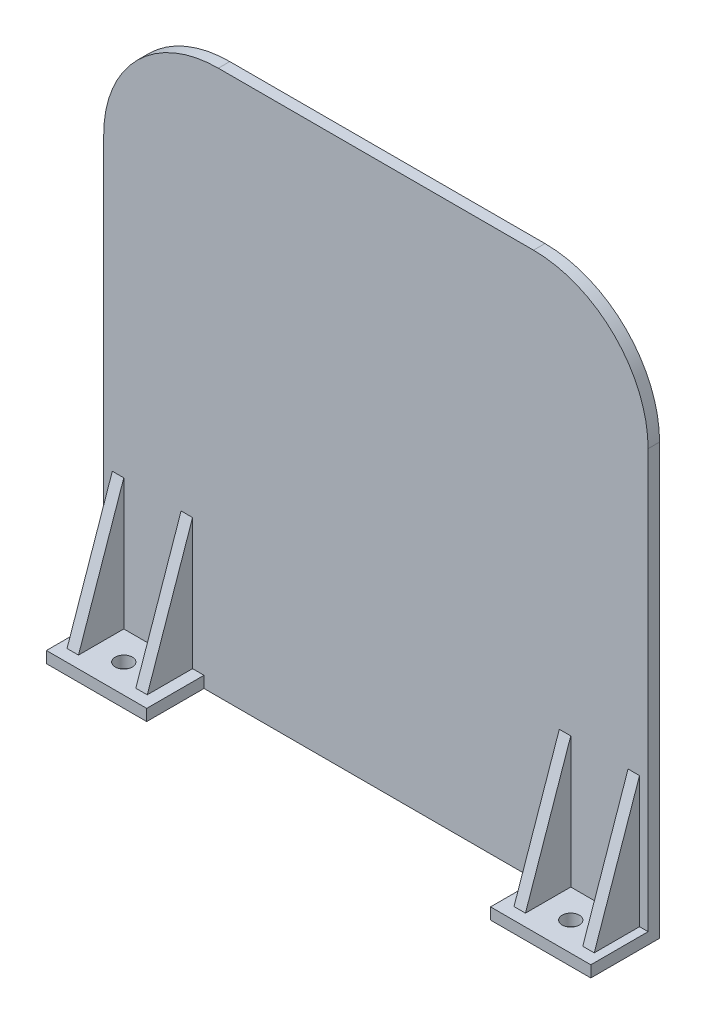
SolidWorks part; units mm, degrees
ref_plane "前视基准面" through (0, 0, 0) normal (0, 0, 1) x (1, 0, 0)
ref_plane "上视基准面" through (0, 0, 0) normal (0, 1, 0) x (1, 0, 0)
ref_plane "右视基准面" through (0, 0, 0) normal (1, 0, 0) x (0, 0, -1)
sketch "草图1" plane through (0, 0, 0) normal (0, 0, 1) x (1, 0, 0)
  line L1 (-47.5, -47.5) -> (47.5, -47.5)
  line L2 (-47.5, -47.5) -> (-47.5, 47.5)
  line L3 (-47.5, 47.5) -> (47.5, 47.5)
  line L4 (47.5, -47.5) -> (47.5, 47.5)
  line L5 (-47.5, -47.5) -> (47.5, 47.5) construction
  line L6 (-47.5, 47.5) -> (47.5, -47.5) construction
  point P0 (0, 0)
  dimension "D1" = 95
  dimension "D2" = 95
extrude "凸台-拉伸1" add sketch "草图1" along normal blind 2
sketch "草图2" plane through (0, 0, 2) normal (0, 0, 1) x (1, 0, 0)
  line L0 (47.5, -47.5) -> (47.5, 47.5) construction
  line L1 (-47.5, -47.5) -> (47.5, -47.5)
  line L2 (-47.5, -47.5) -> (-47.5, -45.5)
  line L3 (-47.5, -45.5) -> (47.5, -45.5)
  line L4 (47.5, -47.5) -> (47.5, -45.5)
  dimension "D1" = 2
extrude "凸台-拉伸2" add sketch "草图2" along normal blind 10
fillet "圆角1" radius 20 2 edges at (47.5, 47.5, 1) (-47.5, 47.5, 1)
sketch "草图3" plane through (0, -45.5, 0) normal (0, 1, 0) x (1, 0, 0)
  line L2 (30, -2) -> (30, -12)
  line L4 (-30, -2) -> (-30, -12)
  line L5 (-30, -2) -> (30, -2)
  line L6 (47.5, -2) -> (-47.5, -2) construction
  line L10 (-30, -2) -> (-30, -12)
  line L12 (47.5, -12) -> (-47.5, -12) construction
  line L16 (30, -2) -> (30, -12)
  line L17 (30, -12) -> (-30, -12)
  dimension "D1" = 60
  dimension "D2" = 30
extrude "切除-拉伸1" cut sketch "草图3" against normal through all
sketch "草图5" plane through (0, 0, 0) normal (1, 0, 0) x (0, 0, -1)
  line L3 (-1.4999, -46.2136) -> (-1.4999, -21.2136)
  line L4 (-1.4999, -21.2136) -> (-10.1517, -46.2136)
  line L5 (-10.1517, -46.2136) -> (-1.4999, -46.2136)
  dimension "D1" = 25
extrude "凸台-拉伸3" add sketch "草图5" along normal mid plane 2 from offset 33 contours L4 L5 L3
pattern_linear "阵列(线性)1" count 2 spacing 12 along (1, 0, 0) of "凸台-拉伸3"
mirror "镜向1" about plane through (0, 0, 0) normal (1, 0, 0) of "阵列(线性)1", "凸台-拉伸3"
sketch "草图7" plane through (0, -45.5, 0) normal (0, 1, 0) x (1, 0, 0)
  line L6 (0, 0) -> (0, -15.4369) construction
  line L7 (-34, -2) -> (-44, -2) construction
  circle A0 centre (-39, -7) radius 1.5
  circle A1 centre (39, -7) radius 1.5
  dimension "D1" = 3
  dimension "D2" = 78
  dimension "D3" = 5
extrude "切除-拉伸2" cut sketch "草图7" against normal blind 2
